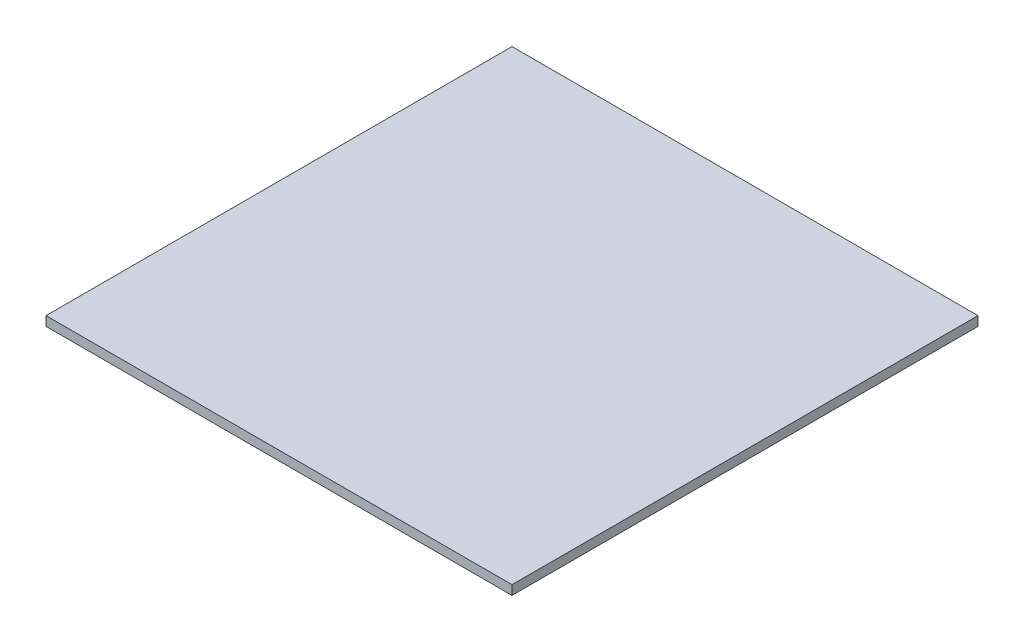
SolidWorks part; units mm, degrees
ref_plane "Front Plane" through (0, 0, 0) normal (0, 0, 1) x (1, 0, 0)
ref_plane "Top Plane" through (0, 0, 0) normal (0, 1, 0) x (1, 0, 0)
ref_plane "Right Plane" through (0, 0, 0) normal (1, 0, 0) x (0, 0, -1)
sketch "Sketch1" plane through (0, 0, 0) normal (0, 1, 0) x (1, 0, 0)
  line L0 (-250, -250) -> (250, -250)
  line L1 (-250, -250) -> (-250, 250)
  line L2 (250, -250) -> (250, 250)
  line L3 (-250, 250) -> (250, 250)
  line L4 (-250, -250) -> (250, 250) construction
  line L5 (250, -250) -> (-250, 250) construction
  point P1 (0, 0)
  dimension "D1" = 500
  dimension "D2" = 500
extrude "Boss-Extrude1" add sketch "Sketch1" along normal blind 10
sketch "Sketch2" plane through (0, 0, 0) normal (0, -1, 0) x (1, 0, 0)
  line L0 (50, -100) -> (50, 100)
  line L1 (50, -100) -> (-50, -100)
  line L2 (50, 100) -> (-50, 100)
  line L3 (-50, -100) -> (-50, 100)
  line L4 (50, -100) -> (-50, 100) construction
  line L5 (50, 100) -> (-50, -100) construction
  point P1 (0, 0)
  dimension "D1" = 100
  dimension "D2" = 200
extrude "Boss-Extrude2" add sketch "Sketch2" along normal blind 50
sketch "Sketch3" plane through (0, 0, 100) normal (0, 0, 1) x (1, 0, 0)
  line L3 (-45.5, -36) -> (-4.5, -36)
  line L4 (-45.5, -36) -> (-45.5, -14)
  line L5 (-45.5, -14) -> (-4.5, -14)
  line L6 (-4.5, -36) -> (-4.5, -14)
  line L7 (-45.5, -36) -> (-4.5, -14) construction
  line L8 (-45.5, -14) -> (-4.5, -36) construction
  line L9 (45.5, -36) -> (4.5, -36)
  line L10 (45.5, -36) -> (45.5, -14)
  line L11 (45.5, -14) -> (4.5, -14)
  line L12 (4.5, -36) -> (4.5, -14)
  line L13 (45.5, -36) -> (4.5, -14) construction
  line L14 (45.5, -14) -> (4.5, -36) construction
  point P0 (25, -25)
  point P1 (-25, -25)
  point P2 (25, -25)
  point P3 (-25, -25)
  dimension "D1" = 41
  dimension "D2" = 22
extrude "Cut-Extrude1" cut sketch "Sketch3" against normal up to next
